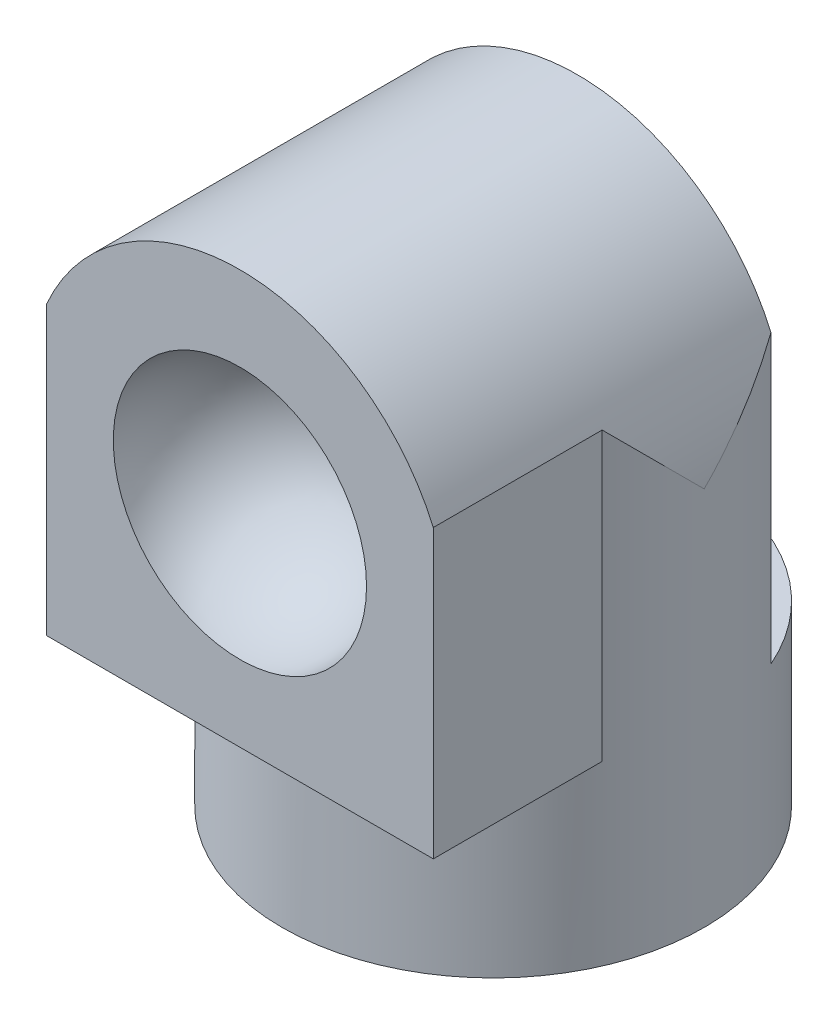
SolidWorks part; units mm, degrees
ref_plane "Front Plane" through (0, 0, 0) normal (0, 0, 1) x (1, 0, 0)
ref_plane "Top Plane" through (0, 0, 0) normal (0, 1, 0) x (1, 0, 0)
ref_plane "Right Plane" through (0, 0, 0) normal (1, 0, 0) x (0, 0, -1)
sketch "Sketch1" plane through (0, 0, 0) normal (0, 1, 0) x (1, 0, 0)
  circle A0 centre (0, 0) radius 1
  circle A1 centre (0, 0) radius 2.5
  dimension "D1" = 2
  dimension "D2" = 5
extrude "Boss-Extrude2" add sketch "Sketch1" along normal blind 2.1
sketch "Sketch2" plane through (0, 0, 0) normal (0, 0, 1) x (1, 0, 0)
  line L0 (2.5, 4.5) -> (2.5, 0)
  line L2 (2.5, 0) -> (-2.5, 0)
  line L3 (-2.5, 0) -> (-2.5, 4.5)
  arc A2 (2.5, 4.5) -> (-2.5, 4.5) centre (0, 4.5) ccw
  dimension "D2" = 5
  dimension "D3" = 4.5
  dimension "D4" = 4.5
extrude "Boss-Extrude3" add sketch "Sketch2" along normal mid plane 2
sketch "Sketch4" plane through (0, 0, 0) normal (0, -1, 0) x (1, 0, 0)
  circle A0 centre (0, 0) radius 1
  dimension "D1" = 2
extrude "Cut-Extrude13" cut sketch "Sketch4" against normal blind 2
sketch "Sketch6" plane through (0, 0, 0) normal (0, -1, 0) x (1, 0, 0)
  circle A0 centre (0, 0) radius 2.5
extrude "Cut-Extrude14" cut sketch "Sketch6" against normal through all flip side to cut
sketch "Sketch7" plane through (0, 0, 1) normal (0, 0, 1) x (1, 0, 0)
  line L0 (-2.2913, 2.1) -> (-2.2913, 5.5)
  line L1 (-2.2913, 5.5) -> (-2.2913, 2.1) construction
  line L2 (-2.2913, 2.1) -> (2.2913, 2.1)
  line L3 (2.2913, 2.1) -> (2.2913, 5.5)
  arc A0 (-2.2913, 5.5) -> (-2.5, 4.5) centre (0, 4.5) ccw construction
  arc A1 (-2.2913, 5.5) -> (2.2913, 5.5) centre (0, 4.5) cw
  arc M1 (2.2913, 5.5) -> (-2.2913, 5.5) centre (0, 4.5) ccw
  line M2 (-2.2913, 5.5) -> (-2.2913, 2.1)
  line M3 (-2.2913, 2.1) -> (2.2913, 2.1)
  line M4 (2.2913, 2.1) -> (2.2913, 5.5)
extrude "Boss-Extrude4" add sketch "Sketch7" along normal blind 2 contours M4 M1 M2 M3
sketch "Sketch9" plane through (0, 0, 3) normal (0, 0, 1) x (1, 0, 0)
  line L0 (-1.5, 4.5) -> (1.5, 4.5)
  arc A0 (1.5, 4.5) -> (-1.5, 4.5) centre (0, 4.5) ccw
  dimension "D1" = 3
revolve "Cut-Revolve1" cut sketch "Sketch9" angle 360 about L0
